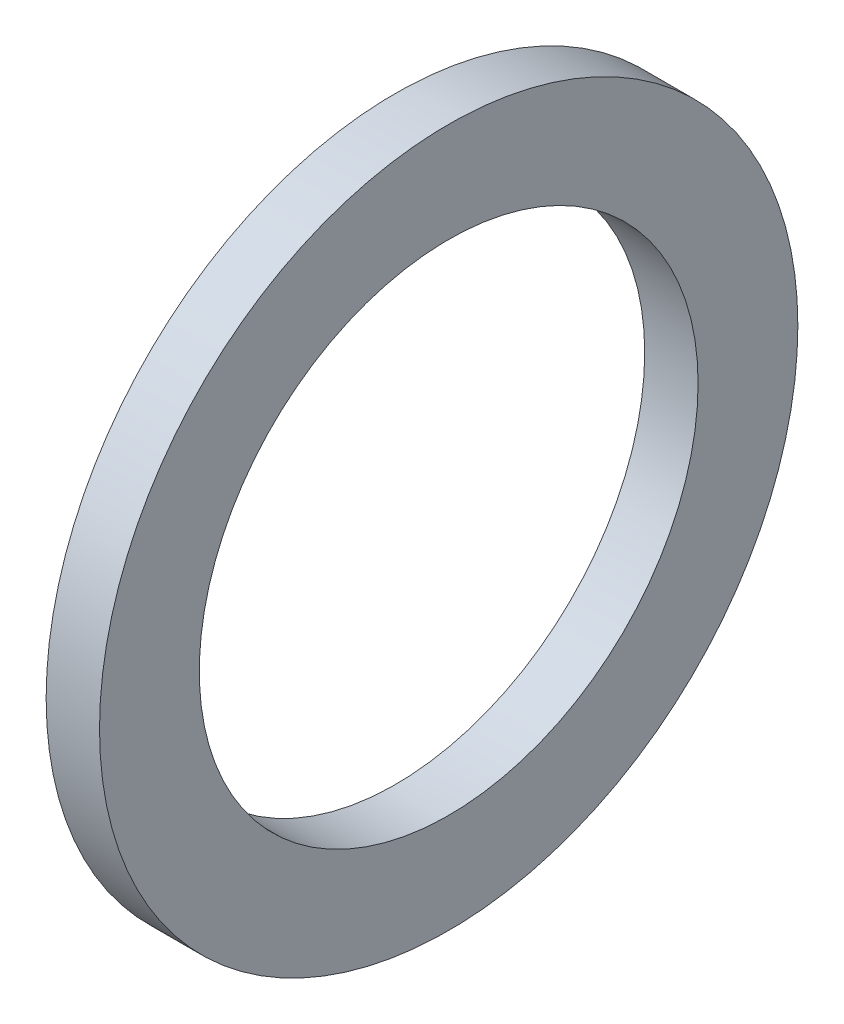
SolidWorks part; units mm, degrees
material "6061-T6 (SS)"
ref_plane "Front Plane" through (0, 0, 0) normal (0, 0, 1) x (1, 0, 0)
ref_plane "Top Plane" through (0, 0, 0) normal (0, 1, 0) x (1, 0, 0)
ref_plane "Right Plane" through (0, 0, 0) normal (1, 0, 0) x (0, 0, -1)
sketch "Sketch1" plane through (0, 0, 0) normal (1, 0, 0) x (0, 0, -1)
  circle A0 centre (0, 0) radius 6.35
  circle A1 centre (0, 0) radius 8.89
  dimension "D1" = 12.7
  dimension "D2" = 2.54
extrude "Boss-Extrude1" add sketch "Sketch1" along normal blind 1.3589
